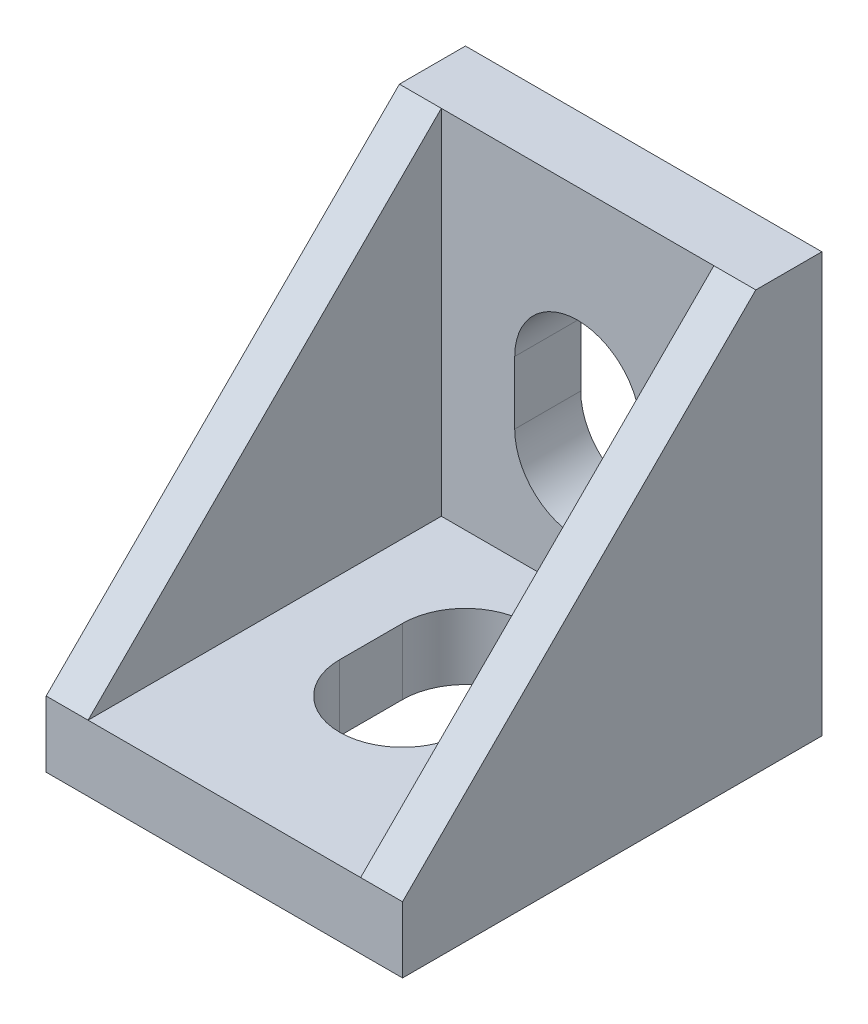
SolidWorks part; units mm, degrees
ref_plane "Front Plane" through (0, 0, 0) normal (0, 0, 1) x (1, 0, 0)
ref_plane "Top Plane" through (0, 0, 0) normal (0, 1, 0) x (1, 0, 0)
ref_plane "Right Plane" through (0, 0, 0) normal (1, 0, 0) x (0, 0, -1)
sketch "Sketch1" plane through (0, 0, 0) normal (0, 1, 0) x (1, 0, 0)
  line L1 (-8.5, -10) -> (8.5, -10)
  line L2 (-8.5, -10) -> (-8.5, 10)
  line L3 (-8.5, 10) -> (8.5, 10)
  line L4 (8.5, -10) -> (8.5, 10)
  line L5 (-8.5, -10) -> (8.5, 10) construction
  line L6 (-8.5, 10) -> (8.5, -10) construction
  point P0 (0, 0)
  dimension "D1" = 20
  dimension "D2" = 17
extrude "Boss-Extrude1" add sketch "Sketch1" along normal blind 3.15
sketch "Sketch2" plane through (0, 3.15, 0) normal (0, 1, 0) x (1, 0, 0)
  line L0 (8.5, -10) -> (8.5, 10) construction
  line L1 (-8.5, 10) -> (8.5, 10)
  line L2 (-8.5, 10) -> (-8.5, 6.85)
  line L3 (-8.5, 6.85) -> (8.5, 6.85)
  line L4 (8.5, 10) -> (8.5, 6.85)
  dimension "D1" = 3.15
extrude "Boss-Extrude2" add sketch "Sketch2" along normal blind 16.85
sketch "Sketch3" plane through (0, 0, 0) normal (0, -1, 0) x (1, 0, 0)
  line L0 (0, 0) -> (0, 1.5) construction
  line L1 (0, 0) -> (0, -1.5) construction
  line L7 (3, 1.5) -> (-3, 1.5)
  line L8 (3, 1.5) -> (3, -1.5)
  line L9 (3, -1.5) -> (-3, -1.5)
  line L10 (-3, 1.5) -> (-3, -1.5)
  circle A0 centre (0, -1.5) radius 3
  circle A1 centre (0, 1.5) radius 3
  dimension "D3" = 6
  dimension "D4" = 6
  dimension "D1" = 1.5
  dimension "D2" = 1.5
extrude "Cut-Extrude1" cut sketch "Sketch3" against normal up to next contours L9 A0 | A1 A0 | A1 L9 A0 | L7 A1 A0 | A1 A0 L8 | L7 A1 | A1 A0 L9 | A1 L10 A0 | A0 A1 L7
sketch "Sketch4" plane through (0, 0, -10) normal (0, 0, -1) x (-1, 0, 0)
  line L0 (0, 0) -> (0, 20) construction
  line L1 (-8.5, 0) -> (8.5, 0) construction
  line L2 (-8.5, 20) -> (8.5, 20) construction
  line L3 (0, 10) -> (0, 8.5) construction
  line L4 (0, 10) -> (0, 11.5) construction
  line L6 (3, 11.5) -> (-3, 11.5)
  line L7 (3, 11.5) -> (3, 8.5)
  line L8 (3, 8.5) -> (-3, 8.5)
  line L9 (-3, 11.5) -> (-3, 8.5)
  circle A0 centre (0, 8.5) radius 3
  circle A1 centre (0, 11.5) radius 3
  dimension "D3" = 6
  dimension "D1" = 1.5
  dimension "D2" = 1.5
extrude "Cut-Extrude2" cut sketch "Sketch4" against normal up to next contours L8 A0 | L6 A1
sketch "Sketch5" plane through (8.5, 0, 0) normal (1, 0, 0) x (0, 0, -1)
  line L0 (6.85, 20) -> (-10, 3.15)
  line L1 (-10, 3.15) -> (6.85, 3.15)
  line L2 (6.85, 3.15) -> (6.85, 20)
extrude "Boss-Extrude3" add sketch "Sketch5" against normal blind 2
sketch "Sketch6" plane through (-8.5, 0, 0) normal (-1, 0, 0) x (0, 0, 1)
  line L0 (10, 3.15) -> (-6.85, 20)
  line L1 (-6.85, 20) -> (-6.85, 3.15)
  line L2 (-6.85, 3.15) -> (10, 3.15)
extrude "Boss-Extrude4" add sketch "Sketch6" against normal blind 2
